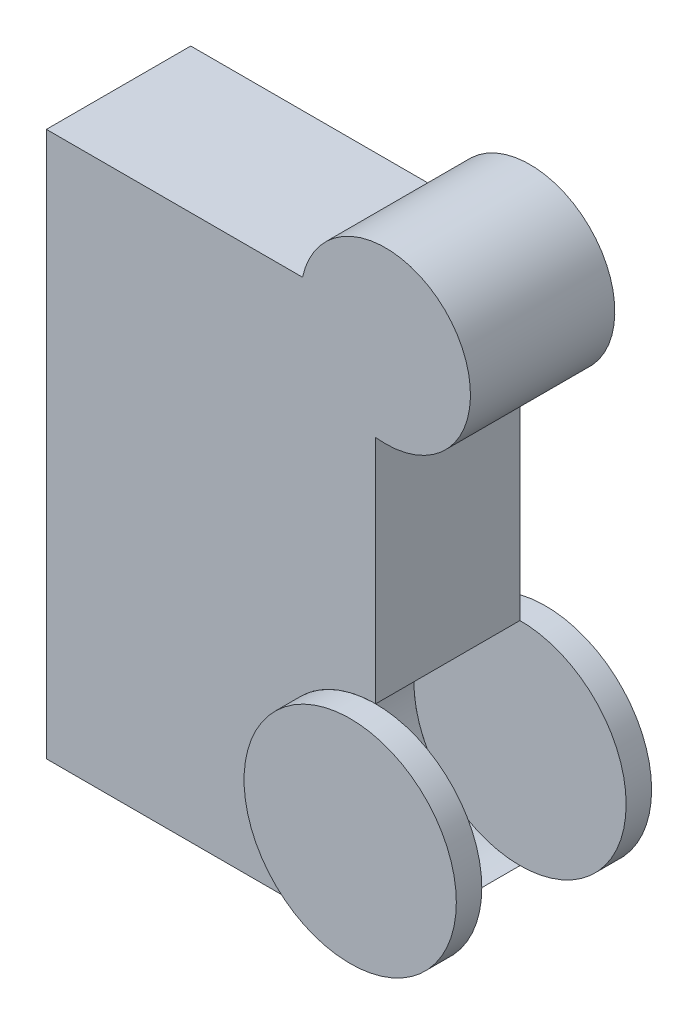
SolidWorks part; units mm, degrees
ref_plane "Alzado" through (0, 0, 0) normal (0, 0, 1) x (1, 0, 0)
ref_plane "Planta" through (0, 0, 0) normal (0, 1, 0) x (1, 0, 0)
ref_plane "Vista lateral" through (0, 0, 0) normal (1, 0, 0) x (0, 0, -1)
sketch "Croquis1" plane through (0, 0, 0) normal (0, 0, 1) x (1, 0, 0)
  line L1 (-20, -31.0927) -> (18.7796, -31.0927)
  line L2 (-20, -31.0927) -> (-20, 33.1132)
  line L3 (-20, 33.1132) -> (10.1689, 33.1132)
  line L4 (18.7796, -31.0927) -> (18.7796, 21.0745)
  line L5 (-20, -31.0927) -> (19.9445, 31.0064) construction
  line L6 (-20, 33.1132) -> (18.7796, -31.0927) construction
  arc A0 (18.7796, 21.0745) -> (10.1689, 33.1132) centre (19.9445, 31.0064) ccw
  circle A1 centre (18.7796, -18.5927) radius 12.5
  point P0 (0, 0)
  dimension "D2" = 20
  dimension "D3" = 25
  dimension "D1" = 62.11
  dimension "D4" = 40
  dimension "D6" = 20
extrude "Saliente-Extruir1" add sketch "Croquis1" along normal mid plane 17 contours A1 L4 A0 L3 L2 L1
sketch "Croquis2" plane through (0, 0, 8.5) normal (0, 0, 1) x (1, 0, 0)
  circle A0 centre (18.7796, -18.5927) radius 12.5
  arc A1 (18.7796, -6.0927) -> (18.7796, -31.0927) centre (18.7796, -18.5927) ccw construction
  dimension "D1" = 25
extrude "Saliente-Extruir2" add sketch "Croquis2" along normal blind 3 separate body
ref_plane "Plano1" through (0, 0, 0) normal (0, 0, -1) x (-1, 0, 0)
mirror "Simetría2" about plane through (0, 0, 0) normal (0, 0, -1) of bodies 102
